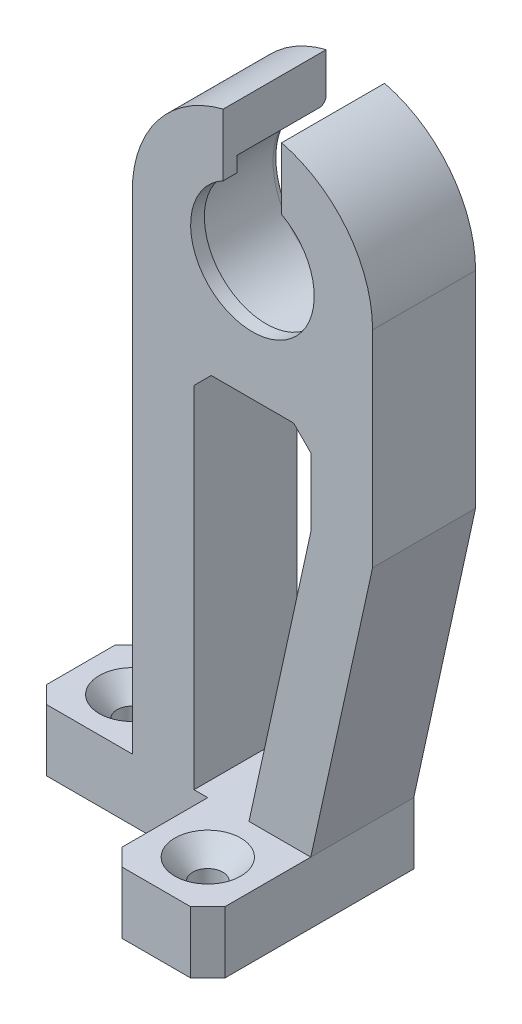
SolidWorks part; units mm, degrees
ref_plane "Front Plane" through (0, 0, 0) normal (0, 0, 1) x (1, 0, 0)
ref_plane "Top Plane" through (0, 0, 0) normal (0, 1, 0) x (1, 0, 0)
ref_plane "Right Plane" through (0, 0, 0) normal (1, 0, 0) x (0, 0, -1)
sketch "Sketch1" plane through (0, 0, 0) normal (0, 0, 1) x (1, 0, 0)
  line L0 (17.5, 0) -> (-17.5, 0)
  line L9 (-8.5, -17.5) -> (8.5, -17.5)
  line L22 (-8.5, -17.5) -> (-8.5, -71)
  line L23 (0, 0) -> (0, -17.5) construction
  line L24 (-4.25, 7.5) -> (4.25, 7.5)
  line L31 (-4.25, 7.5) -> (-4.25, 17.5)
  line L32 (-4.25, 17.5) -> (4.25, 17.5)
  line L33 (4.25, 17.5) -> (4.25, 7.5)
  line L35 (8.5, -17.5) -> (8.5, -30)
  line L36 (17.5, -30) -> (17.5, 0)
  line L37 (8.5, -30) -> (17.5, -30)
  line L41 (8.5, -71) -> (8.5, -80)
  line L42 (8.5, -30) -> (-0.5, -71)
  line L43 (8.5, -71) -> (8.5, -80)
  line L44 (17.5, -30) -> (8.5, -71)
  line L45 (-17.5, -80) -> (-17.5, 0)
  line L46 (-17.5, -80) -> (8.5, -80)
  line L47 (-8.5, -71) -> (-0.5, -71)
  line L49 (-17.5, -80) -> (-32.5, -80)
  line L50 (-17.5, -80) -> (-17.5, -71)
  line L51 (-17.5, -71) -> (-32.5, -71)
  line L52 (-32.5, -80) -> (-32.5, -71)
  circle A0 centre (0, 0) radius 17.5
  circle A1 centre (0, 0) radius 11
  point P4 (0, 0)
  point P31 (0, 11)
  point P38 (0, 7.5)
  dimension "D2" = 22
  dimension "D3" = 35
  dimension "D4" = 80
  dimension "D5" = 9
  dimension "D6" = 9
  dimension "D7" = 15
  dimension "D8" = 30
  dimension "D10" = 8.5
  dimension "D11" = 10
extrude "Boss-Extrude1" add sketch "Sketch1" along normal blind 15 contours L23 A1 L0 A0 | A1 L31 A0 L0 | A1 L0 A0 L33 | A1 L23 A0 L0 | A0 L45 L46 L41 L44 L37 L42 L47 L22 L9 | A0 L9 L35 L37 L36 | L52 L49 L45 L51
ref_plane "Plane1" through (-25, 0, 0) normal (1, 0, 0) x (0, 0, -1)
sketch "Sketch6" plane through (0, 0, 15) normal (0, 0, -1) x (-1, 0, 0)
  line L0 (-4.25, 10.1458) -> (-4.25, 7.9333)
  line L5 (4.25, 10.1458) -> (4.25, 7.9333)
  line L6 (4.25, 10.1458) -> (4.25, 16.9761) construction
  line L7 (-4.25, 16.9761) -> (-4.25, 10.1458) construction
  circle A0 centre (0, 0) radius 11
  arc A1 (-4.25, 10.1458) -> (4.25, 10.1458) centre (0, 0) ccw construction
  circle A2 centre (0, 0) radius 9
  arc M68 (-4.25, 10.1458) -> (4.25, 10.1458) centre (0, 0) ccw
  dimension "D1" = 2
extrude "Boss-Extrude3" add sketch "Sketch6" along normal blind 2 contours L0 A2 L5 M68
sketch "Sketch7" plane through (0, 0, 15) normal (0, 0, 1) x (1, 0, 0)
  line L1 (-6.5, -71) -> (8.5, -71)
  line L2 (-6.5, -71) -> (-6.5, -80)
  line L3 (-6.5, -80) -> (8.5, -80)
  line L4 (8.5, -71) -> (8.5, -80)
  line L8 (-8.5, -71) -> (-0.5, -71) construction
  dimension "D1" = 15
extrude "Boss-Extrude4" add sketch "Sketch7" along normal blind 15
ref_plane "Plane3" through (-25, 0, 0) normal (-1, 0, 0) x (0, 0, 1)
sketch "Sketch11" plane through (-25, 0, 0) normal (-1, 0, 0) x (0, 0, 1)
  line L0 (7.5, -71) -> (7.5, -80)
  line L1 (15, -71) -> (0, -71) construction
  line L2 (15, -80) -> (0, -80) construction
  line L3 (7.5, -71) -> (12.3079, -71)
  line L4 (12.3079, -71) -> (9.7, -74)
  line L5 (9.7, -74) -> (9.7, -80)
  line L6 (9.7, -80) -> (7.5, -80)
  line L7 (9.7, -74) -> (7.5, -74) construction
  dimension "D1" = 3
  dimension "D2" = 131
  dimension "D3" = 2.2
revolve "Cut-Revolve4" cut sketch "Sketch11" angle 360 about L0
ref_plane "Plane2" through (0, 0, 22.5) normal (0, 0, 1) x (1, 0, 0)
sketch "Sketch10" plane through (0, 0, 22.5) normal (0, 0, 1) x (1, 0, 0)
  line L0 (1, -71) -> (5.8079, -71)
  line L1 (8.5, -71) -> (-6.5, -71) construction
  line L2 (5.8079, -71) -> (3.2, -74)
  line L3 (3.2, -74) -> (3.2, -80)
  line L4 (-6.5, -80) -> (8.5, -80) construction
  line L5 (3.2, -80) -> (1, -80)
  line L6 (1, -80) -> (1, -71)
  line L7 (3.2, -74) -> (1, -74) construction
  dimension "D1" = 3
  dimension "D2" = 2.2
  dimension "D3" = 131
revolve "Cut-Revolve3" cut sketch "Sketch10" angle 360 about L6
fillet "Fillet1" radius 1 1 edges at (0, -11, 0)
chamfer "Chamfer1" distance 2.5 angle 45 6 edges at (-8.5, -17.5, 7.5) (8.5, -75.5, 30) (-6.5, -75.5, 30) (8.5, -17.5, 7.5) (-32.5, -75.5, 0) (-32.5, -75.5, 15)
